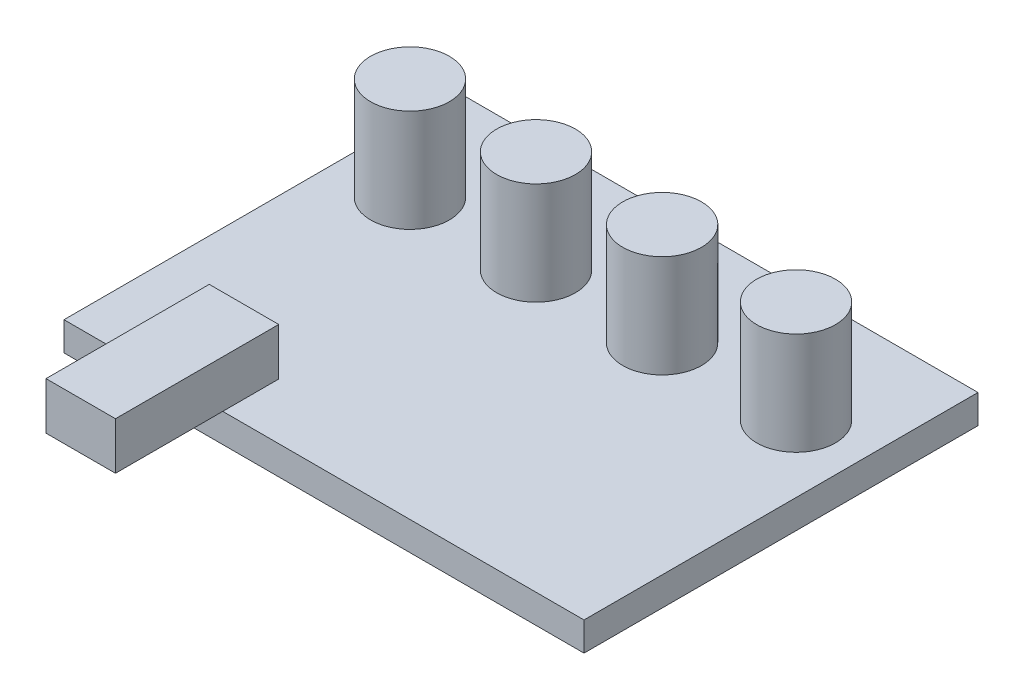
SolidWorks part; units mm, degrees
ref_plane "Front Plane" through (0, 0, 0) normal (0, 0, 1) x (1, 0, 0)
ref_plane "Top Plane" through (0, 0, 0) normal (0, 1, 0) x (1, 0, 0)
ref_plane "Right Plane" through (0, 0, 0) normal (1, 0, 0) x (0, 0, -1)
sketch "Sketch1" plane through (0, 0, 0) normal (0, 1, 0) x (1, 0, 0)
  line L5 (-32.9989, 24.3) -> (32.9989, 24.3)
  line L6 (0, 0) -> (0, 24.3) construction
  line L8 (0, 0) -> (0, -34.8967) construction
  line L25 (32.9989, -25.7) -> (-32.9989, -25.7)
  line L27 (32.9989, 24.3) -> (32.9989, -25.7)
  line L31 (-32.9989, 24.3) -> (-32.9989, -25.7)
  point P7 (0, -25.7)
  dimension "D1" = 25.7
  dimension "D2" = 32.9989
  dimension "D3" = 24.3
extrude "Boss-Extrude1" add sketch "Sketch1" along normal blind 3.65
sketch "Sketch2" plane through (0, 3.65, 0) normal (0, 1, 0) x (1, 0, 0)
  line L0 (-29.5, 9.7116) -> (-34.5, 9.7116) construction
  line L2 (29.5, 9.7116) -> (34.5, 9.7116) construction
  line L3 (34.5, -30.6935) -> (34.5, 29.3065) construction
  line L4 (-24.5, 9.7116) -> (-8.5, 9.7116) construction
  line L5 (-8.5, 9.7116) -> (7.5, 9.7116) construction
  line L6 (7.5, 9.7116) -> (24.5, 9.7116) construction
  line L7 (-34.5, 29.3065) -> (-34.5, -30.6935) construction
  circle A0 centre (-24.5, 9.7116) radius 5
  circle A1 centre (-8.5, 9.7116) radius 5
  circle A2 centre (7.5, 9.7116) radius 5
  circle A3 centre (24.5, 9.7116) radius 5
  dimension "D1" = 10
  dimension "D2" = 5
  dimension "D3" = 5
  dimension "D4" = 17
extrude "Boss-Extrude2" add sketch "Sketch2" along normal blind 13
sketch "Sketch3" plane through (0, 3.65, 0) normal (0, 1, 0) x (1, 0, 0)
  line L1 (-21.666, -18.5966) -> (-12.8497, -18.5966)
  line L2 (-21.666, -18.5966) -> (-21.666, -39.3148)
  line L3 (-21.666, -39.3148) -> (-12.8497, -39.3148)
  line L4 (-12.8497, -18.5966) -> (-12.8497, -39.3148)
extrude "Boss-Extrude3" add sketch "Sketch3" along normal blind 6
